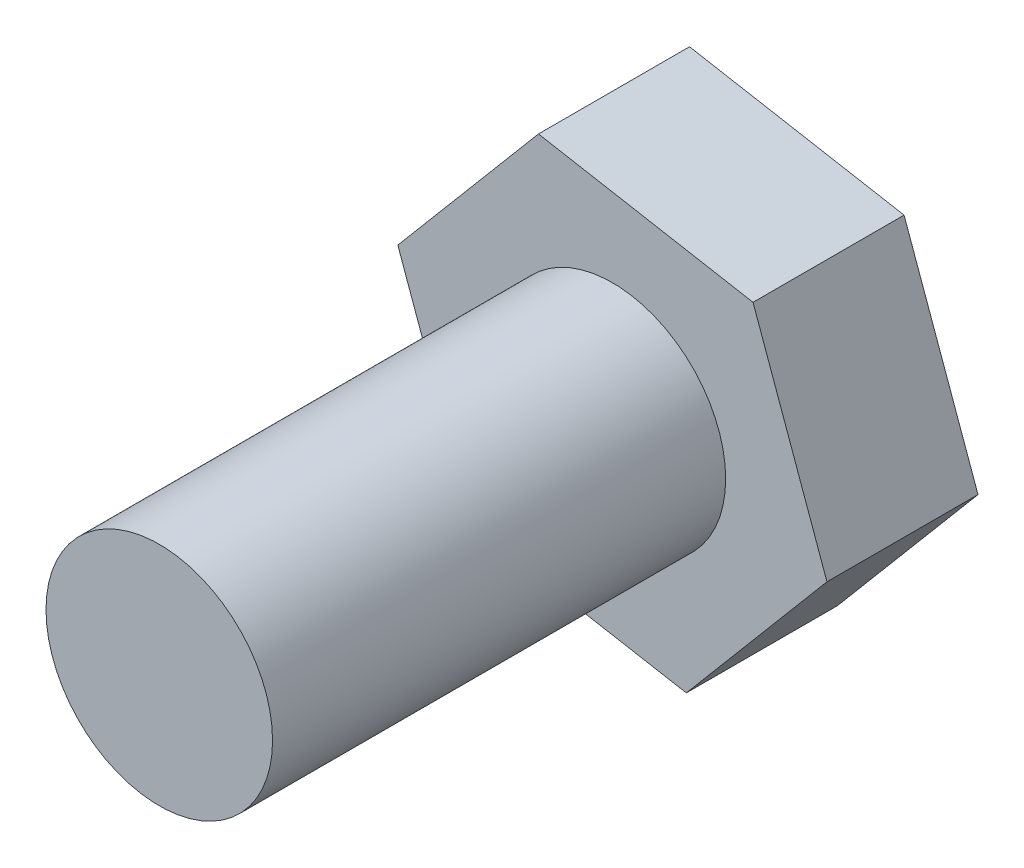
SolidWorks part; units mm, degrees
ref_plane "正面" through (0, 0, 0) normal (0, 0, 1) x (1, 0, 0)
ref_plane "平面" through (0, 0, 0) normal (0, 1, 0) x (1, 0, 0)
ref_plane "右側面" through (0, 0, 0) normal (1, 0, 0) x (0, 0, -1)
sketch "ｽｹｯﾁ1" plane through (0, 0, 0) normal (0, 0, 1) x (1, 0, 0)
  line L1 (-3.7247, -4.4113) -> (1.9579, -5.4314)
  line L2 (1.9579, -5.4314) -> (5.6827, -1.0201)
  line L3 (5.6827, -1.0201) -> (3.7247, 4.4113)
  line L4 (3.7247, 4.4113) -> (-1.9579, 5.4314)
  line L5 (-1.9579, 5.4314) -> (-5.6827, 1.0201)
  line L6 (-5.6827, 1.0201) -> (-3.7247, -4.4113)
  circle A0 centre (0, 0) radius 5 construction
  dimension "D1" = 10
extrude "ﾎﾞｽ - 押し出し1" add sketch "ｽｹｯﾁ1" along normal blind 4
sketch "ｽｹｯﾁ2" plane through (0, 0, 4) normal (0, 0, 1) x (1, 0, 0)
  circle A0 centre (0, 0) radius 3
  dimension "D1" = 6
extrude "ﾎﾞｽ - 押し出し2" add sketch "ｽｹｯﾁ2" along normal blind 12
cosmetic thread "ねじ山1" parameters "D2"=3
